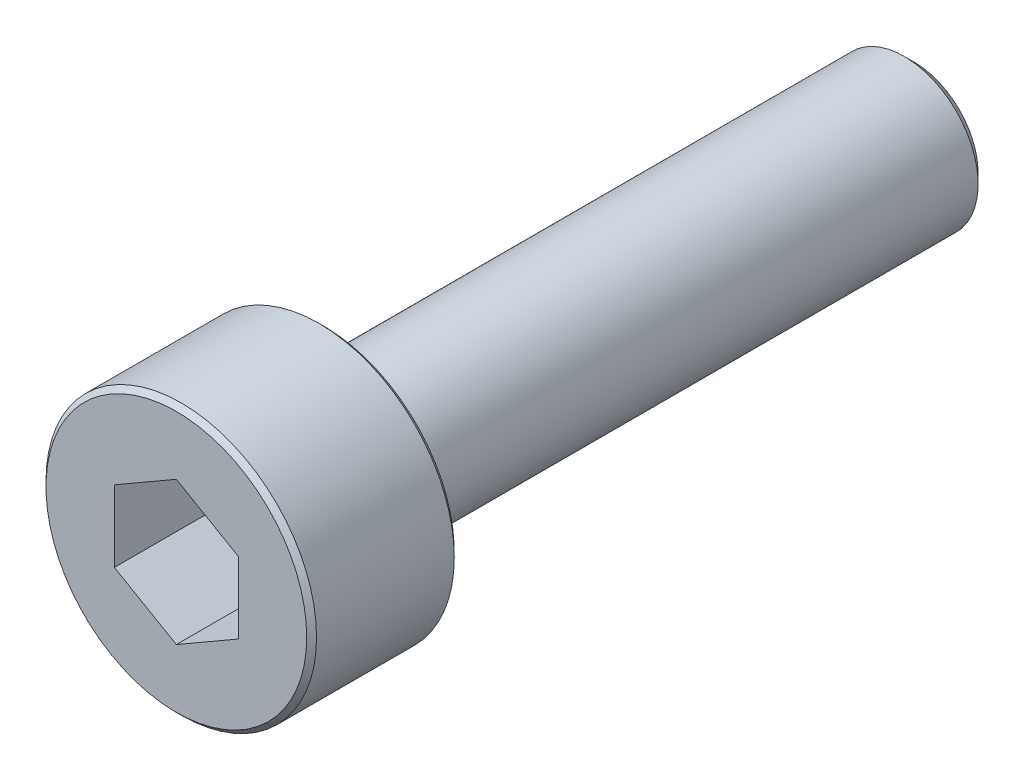
SolidWorks part; units mm, degrees
ref_plane "前视基准面" through (0, 0, 0) normal (0, 0, 1) x (1, 0, 0)
ref_plane "上视基准面" through (0, 0, 0) normal (0, 1, 0) x (1, 0, 0)
ref_plane "右视基准面" through (0, 0, 0) normal (1, 0, 0) x (0, 0, -1)
other "Configuration Table"
sketch "草图1" plane through (0, 0, 0) normal (0, 1, 0) x (1, 0, 0)
  line L0 (2.75, -12) -> (0, -12)
  line L1 (0, -12) -> (0, -15)
  line L2 (0, -15) -> (2.75, -15)
  line L3 (2.75, -15) -> (2.75, -12)
  line L4 (0, -12) -> (0, -15) construction
revolve "旋转1" add sketch "草图1" angle 360 about L4
sketch "草图2" plane through (0, 0, 12) normal (0, 0, -1) x (-1, 0, 0)
  circle A0 centre (0, 0) radius 1.5
extrude "凸台-拉伸1" add sketch "草图2" along normal blind 12
sketch "草图3" plane through (0, 0, 15) normal (0, 0, 1) x (1, 0, 0)
  line L0 (-1.26, -0.7275) -> (0, -1.4549)
  line L1 (0, -1.4549) -> (1.26, -0.7275)
  line L2 (1.26, -0.7275) -> (1.26, 0.7275)
  line L3 (1.26, 0.7275) -> (0, 1.4549)
  line L4 (0, 1.4549) -> (-1.26, 0.7275)
  line L5 (-1.26, 0.7275) -> (-1.26, -0.7275)
extrude "切除-拉伸1" cut sketch "草图3" against normal blind 2.25
chamfer "倒角1" distance 0.1 angle 45 2 edges at (2.75, 0, 12) (2.75, 0, 15)
chamfer "倒角2" distance 0.2 angle 45 1 edges at (-1.5, 0, 0)
